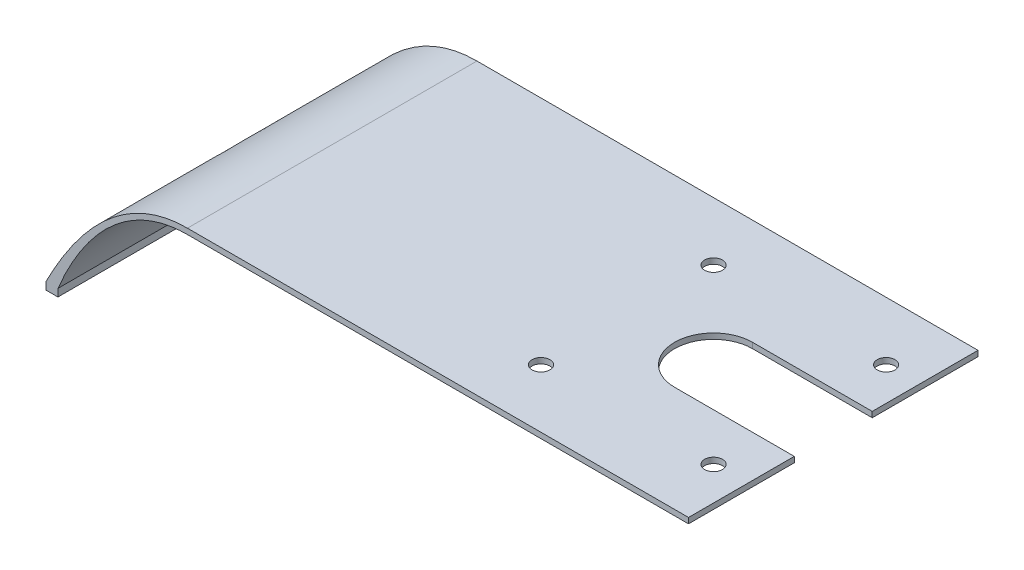
SolidWorks part; units mm, degrees
ref_plane "前视基准面" through (0, 0, 0) normal (0, 0, 1) x (1, 0, 0)
ref_plane "上视基准面" through (0, 0, 0) normal (0, 1, 0) x (1, 0, 0)
ref_plane "右视基准面" through (0, 0, 0) normal (1, 0, 0) x (0, 0, -1)
sketch "草图2" plane through (0, 0, 0) normal (0, 0, 1) x (1, 0, 0)
  line L0 (0, 21) -> (90, 21)
  line L1 (0, 20) -> (90, 20)
  line L3 (90, 20) -> (90, 21)
  line L4 (-25.4099, 0) -> (-25.4099, -1.3441)
  line L5 (-25.4099, -1.3441) -> (-23.2651, -1.3441)
  line L6 (-23.2651, -1.3441) -> (-23.2651, 0)
  arc A2 (-20, 0) -> (0, 20) centre (0, 0) cw construction
  arc A3 (-21, 0) -> (0, 21) centre (0, 0) cw construction
  spline S0 degree 3 poles (0, 20) (-11.9188, 20) (-19.3651, 9.4254) (-23.2651, 0) knots 0 0 0 0 1 1 1 1
  spline S1 degree 3 poles (0, 21) (-12.5146, 21) (-20.5853, 9.3935) (-25.4099, 0) knots 0 0 0 0 1 1 1 1
  dimension "D3" = 1
  dimension "D2" = 90
  dimension "D1" = 1
extrude "凸台-拉伸1" add sketch "草图2" along normal blind 52
sketch "草图3" plane through (0, 21, 0) normal (0, 1, 0) x (1, 0, 0)
  line L0 (90, -26) -> (52.6876, -26) construction
  line L1 (90, -52) -> (90, 0) construction
  line L2 (68.5, 2.5645) -> (68.5, -61.558) construction
  line L3 (90, -19) -> (68.5, -19)
  line L4 (68.5, -33) -> (90, -33)
  line L5 (90, -19) -> (90, -33)
  circle A0 centre (84, -10.5) radius 1.6
  circle A1 centre (84, -41.5) radius 1.6
  circle A2 centre (53, -41.5) radius 1.6
  circle A3 centre (53, -10.5) radius 1.6
  arc A4 (68.5, -19) -> (68.5, -33) centre (68.5, -26) ccw
  point P15 (0, 0)
  dimension "D1" = 3.2
  dimension "D2" = 31
  dimension "D3" = 31
  dimension "D4" = 6
  dimension "D5" = 7
extrude "切除-拉伸1" cut sketch "草图3" against normal blind 52
